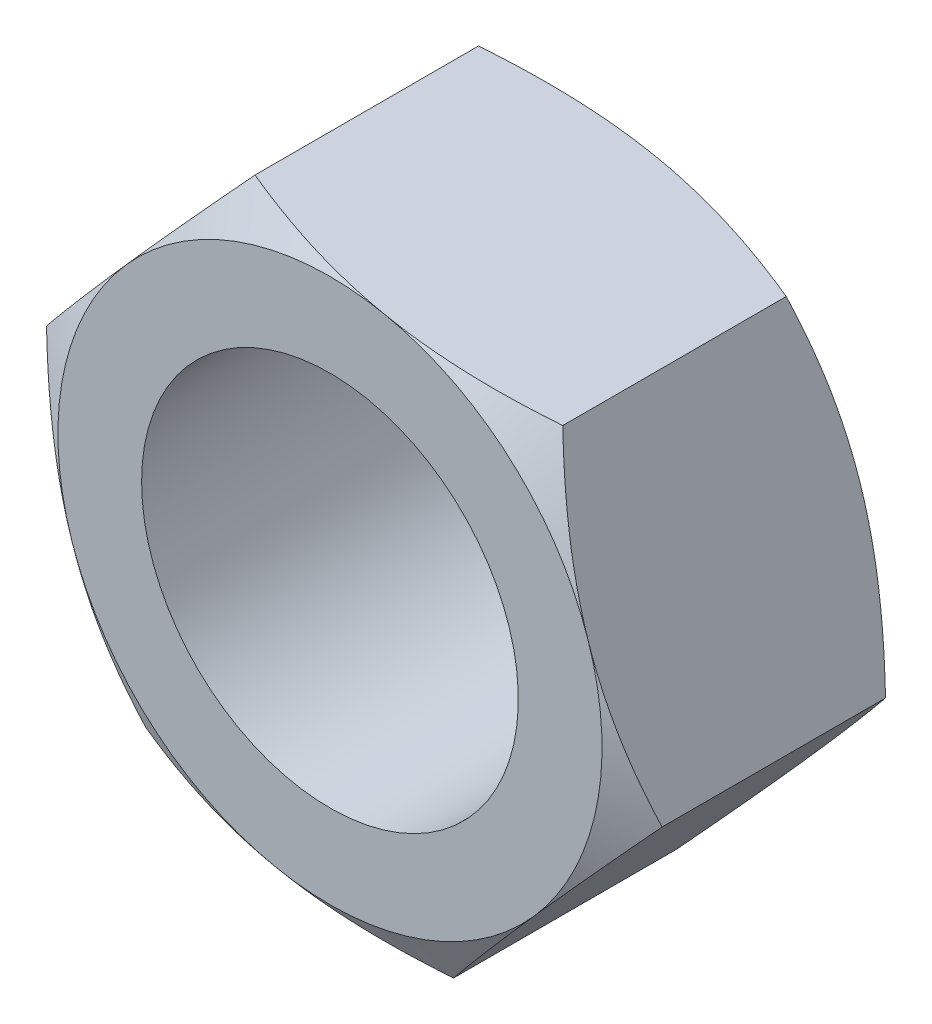
SolidWorks part; units mm, degrees
ref_plane "Front Plane" through (0, 0, 0) normal (0, 0, 1) x (1, 0, 0)
ref_plane "Top Plane" through (0, 0, 0) normal (0, 1, 0) x (1, 0, 0)
ref_plane "Right Plane" through (0, 0, 0) normal (1, 0, 0) x (0, 0, -1)
sketch "Sketch1" plane through (0, 0, 0) normal (0, 0, 1) x (1, 0, 0)
  line L1 (4.9812, 5.6144) -> (-2.3716, 7.121)
  line L2 (-2.3716, 7.121) -> (-7.3528, 1.5066)
  line L3 (-7.3528, 1.5066) -> (-4.9812, -5.6144)
  line L4 (-4.9812, -5.6144) -> (2.3716, -7.121)
  line L5 (2.3716, -7.121) -> (7.3528, -1.5066)
  line L6 (7.3528, -1.5066) -> (4.9812, 5.6144)
  circle A0 centre (0, 0) radius 6.5 construction
  dimension "D1" = 13
extrude "Boss-Extrude1" add sketch "Sketch1" along normal blind 6.5
sketch "Sketch2" plane through (0, 0, 6.5) normal (0, 0, 1) x (1, 0, 0)
  line L0 (-2.3716, 7.121) -> (-7.3528, 1.5066) construction
  circle A0 centre (0, 0) radius 6.5
extrude "Cut-Extrude1" cut sketch "Sketch2" against normal blind 6.5 draft 60 flip side to cut
sketch "Sketch3" plane through (0, 0, 0) normal (0, 0, -1) x (-1, 0, 0)
  line L0 (-4.9812, 5.6144) -> (2.3716, 7.121) construction
  circle A0 centre (0, 0) radius 6.5
extrude "Cut-Extrude2" cut sketch "Sketch3" against normal blind 6.5 draft 60 flip side to cut
sketch "Sketch4" plane through (0, 0, 0) normal (0, 0, -1) x (-1, 0, 0)
  circle A0 centre (0, 0) radius 4.5
  dimension "D1" = 9
extrude "Cut-Extrude3" cut sketch "Sketch4" against normal through all
